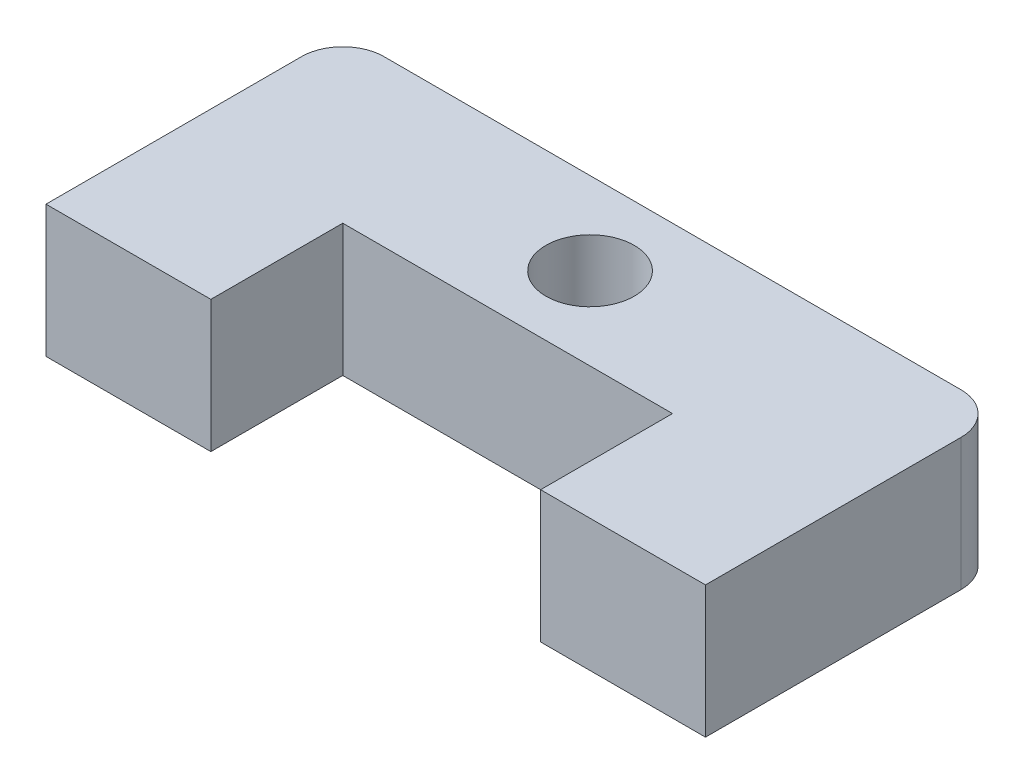
SolidWorks part; units mm, degrees
ref_plane "Front Plane" through (0, 0, 0) normal (0, 0, 1) x (1, 0, 0)
ref_plane "Top Plane" through (0, 0, 0) normal (0, 1, 0) x (1, 0, 0)
ref_plane "Right Plane" through (0, 0, 0) normal (1, 0, 0) x (0, 0, -1)
sketch "Sketch1" plane through (0, 0, 0) normal (0, 1, 0) x (1, 0, 0)
  line L0 (-12.7, -3.175) -> (-12.7, -8.255)
  line L1 (-12.7, -3.175) -> (12.7, -3.175) construction
  line L2 (-12.7, -3.175) -> (-12.7, 3.175)
  line L3 (-12.7, 3.175) -> (12.7, 3.175)
  line L4 (12.7, -3.175) -> (12.7, 3.175)
  line L5 (-12.7, -3.175) -> (12.7, 3.175) construction
  line L6 (-12.7, 3.175) -> (12.7, -3.175) construction
  line L7 (-12.7, -8.255) -> (-6.35, -8.255)
  line L8 (-6.35, -8.255) -> (-6.35, -3.175)
  line L9 (-6.35, -3.175) -> (6.35, -3.175)
  line L10 (6.35, -3.175) -> (6.35, -8.255)
  line L11 (6.35, -8.255) -> (12.7, -8.255)
  line L12 (12.7, -8.255) -> (12.7, -3.175)
  circle A0 centre (0, 0) radius 1.7
  point P0 (0, 0)
  dimension "D5" = 3.4
  dimension "D1" = 6.35
  dimension "D2" = 25.4
  dimension "D3" = 6.35
  dimension "D4" = 5.08
extrude "Boss-Extrude1" add sketch "Sketch1" along normal blind 5.08
fillet "Fillet1" radius 1.5875 2 edges at (12.7, 2.54, -3.175) (-12.7, 2.54, -3.175)
